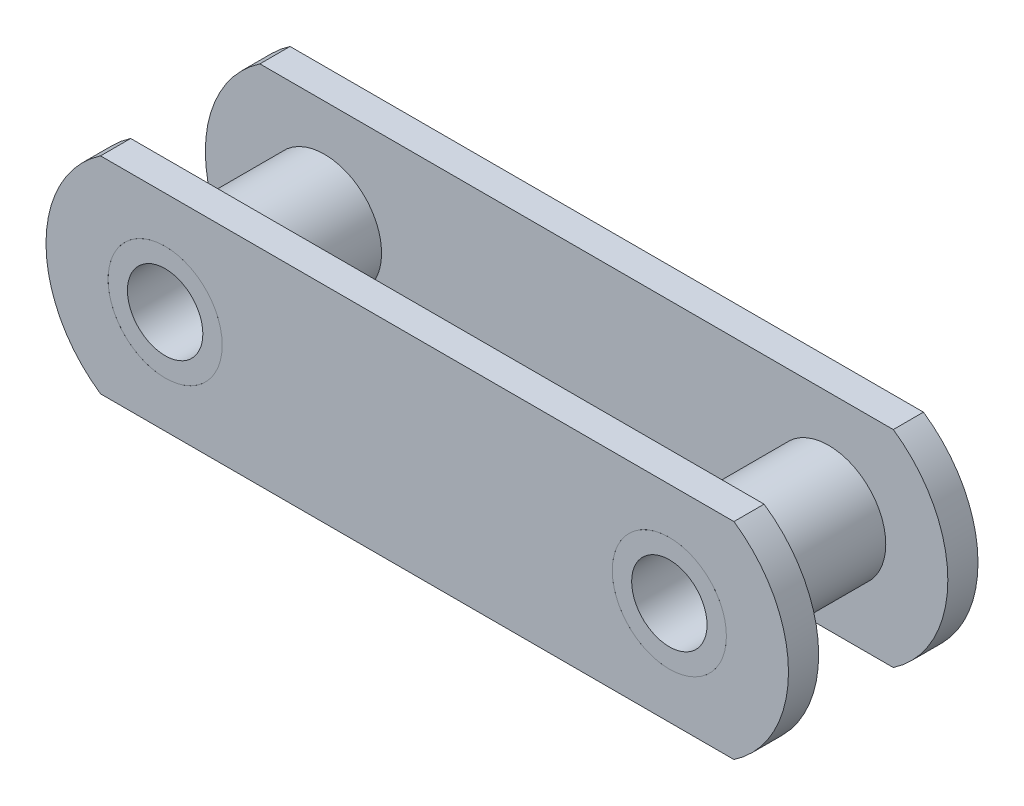
SolidWorks part; units mm, degrees
ref_plane "Front Plane" through (0, 0, 0) normal (0, 0, 1) x (1, 0, 0)
ref_plane "Top Plane" through (0, 0, 0) normal (0, 1, 0) x (1, 0, 0)
ref_plane "Right Plane" through (0, 0, 0) normal (1, 0, 0) x (0, 0, -1)
sketch "Sketch1" plane through (0, 0, 0) normal (0, 0, 1) x (1, 0, 0)
  line L0 (0, 0) -> (74.1587, 0) construction
  line L1 (-63, 20.5) -> (63, 20.5)
  line L2 (-63, -20.5) -> (63, -20.5)
  arc A0 (-63, 20.5) -> (-63, -20.5) centre (-49.0586, 0) ccw
  arc A1 (63, 20.5) -> (63, -20.5) centre (49.0586, 0) cw
  point P5 (0, 20.5)
  point P10 (-73.85, 0)
  point P11 (73.85, 0)
  dimension "D1" = 41
  dimension "D2" = 126
  dimension "D3" = 147.7
extrude "Boss-Extrude1" add sketch "Sketch1" against normal blind 6 from offset 18.85
sketch "Sketch2" plane through (0, 0, 0) normal (0, 0, 1) x (1, 0, 0)
  line L0 (0, 0) -> (0, 45.4415) construction
  circle A0 centre (-50.15, 0) radius 27.5 construction
  circle A1 centre (50.15, 0) radius 27.5 construction
  circle A2 centre (-50.15, 0) radius 7.5
  circle A3 centre (50.15, 0) radius 7.5
  dimension "D1" = 155.3
  dimension "D2" = 55
  dimension "D3" = 15
extrude "Cut-Extrude2" cut sketch "Sketch2" along normal through all
mirror "Mirror1" about plane through (0, 0, 0) normal (0, 0, 1) of bodies 102
sketch "Sketch3" plane through (0, 0, 0) normal (0, 0, 1) x (1, 0, 0)
  circle A0 centre (-50.15, 0) radius 11.35
  circle A1 centre (50.15, 0) radius 11.35
  dimension "D1" = 22.7
extrude "Cut-Extrude3" cut sketch "Sketch3" against normal through all both and the other way through all
sketch "Sketch4" plane through (0, 0, 0) normal (0, 0, 1) x (1, 0, 0)
  circle A0 centre (-50.15, 0) radius 7.5 construction
  circle A1 centre (-50.15, 0) radius 11.35 construction
  circle A2 centre (-50.15, 0) radius 7.5
  circle A3 centre (-50.15, 0) radius 11.35
extrude "Boss-Extrude2" add sketch "Sketch4" along normal up to surface and the other way up to surface separate body
mirror "Mirror2" about plane through (0, 0, 0) normal (1, 0, 0) of bodies 106
